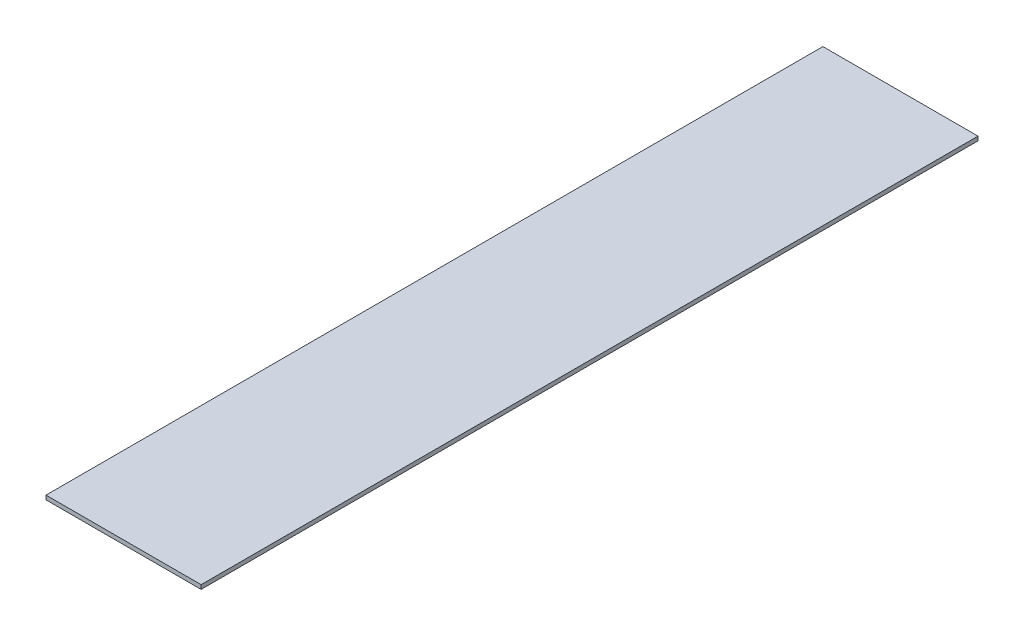
SolidWorks part; units mm, degrees
material "CA"
ref_plane "Front Plane" through (0, 0, 0) normal (0, 0, 1) x (1, 0, 0)
ref_plane "Top Plane" through (0, 0, 0) normal (0, 1, 0) x (1, 0, 0)
ref_plane "Right Plane" through (0, 0, 0) normal (1, 0, 0) x (0, 0, -1)
sketch "Sketch1" plane through (0, 0, 0) normal (0, 1, 0) x (1, 0, 0)
  line L1 (0, 0) -> (113, 0)
  line L2 (0, 0) -> (0, 566)
  line L3 (0, 566) -> (113, 566)
  line L4 (113, 0) -> (113, 566)
  dimension "D1" = 113
  dimension "D2" = 566
extrude "Boss-Extrude1" add sketch "Sketch1" along normal blind 3
